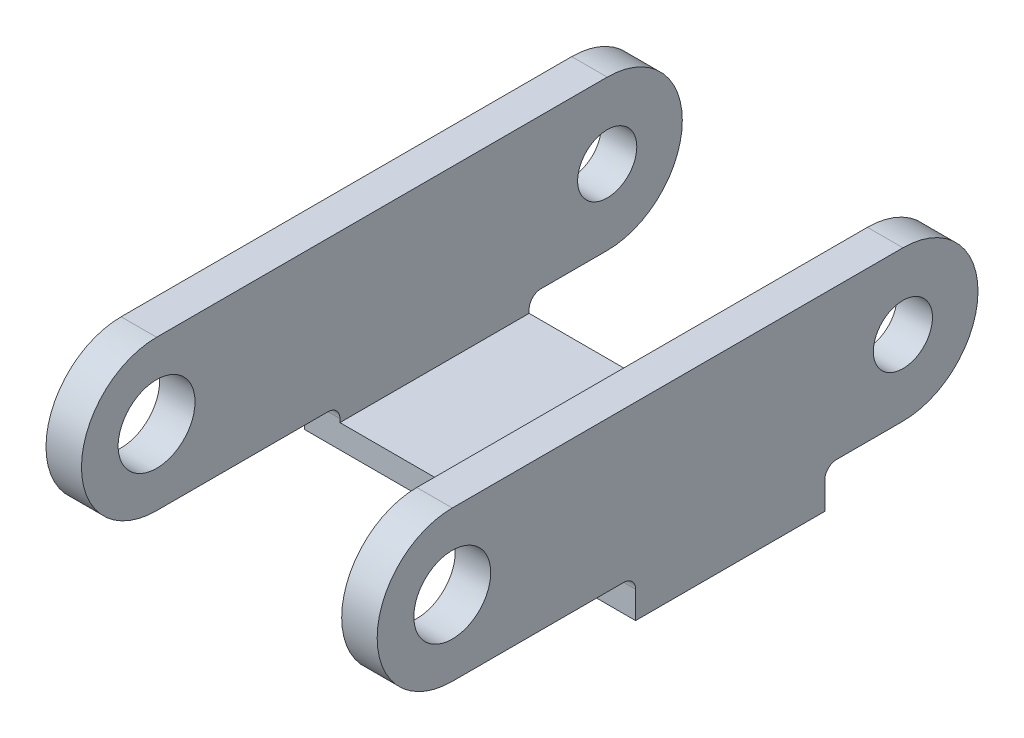
SolidWorks part; units mm, degrees
ref_plane "Front Plane" through (0, 0, 0) normal (0, 0, 1) x (1, 0, 0)
ref_plane "Top Plane" through (0, 0, 0) normal (0, 1, 0) x (1, 0, 0)
ref_plane "Right Plane" through (0, 0, 0) normal (1, 0, 0) x (0, 0, -1)
sketch "Sketch1" plane through (0, 0, 0) normal (1, 0, 0) x (0, 0, -1)
  line L1 (0, 6.35) -> (38.1, 6.35)
  line L3 (15.5, -7.35) -> (15.5, -9.65)
  line L4 (15.5, -9.65) -> (31.5, -9.65)
  line L5 (0, -6.35) -> (14.5, -6.35)
  line L6 (31.5, -9.65) -> (31.5, -7.35)
  line L7 (32.5, -6.35) -> (38.1, -6.35)
  arc A0 (0, 6.35) -> (0, -6.35) centre (0, 0) ccw
  circle A1 centre (0, 0) radius 3.25
  circle A2 centre (38.1, 0) radius 2.5
  arc A3 (38.1, -6.35) -> (38.1, 6.35) centre (38.1, 0) ccw
  arc A4 (15.5, -7.35) -> (14.5, -6.35) centre (14.5, -7.35) ccw
  arc A5 (32.5, -6.35) -> (31.5, -7.35) centre (32.5, -7.35) ccw
  point P10 (31.5, -6.35)
  point P16 (0, 0)
  dimension "D1" = 6.5
  dimension "D2" = 6.35
  dimension "D3" = 1
  dimension "D5" = 5
  dimension "D7" = 1
  dimension "D4" = 38.1
  dimension "D6" = 9.65
  dimension "D8" = 16
  dimension "D9" = 15.5
extrude "Boss-Extrude1" add sketch "Sketch1" along normal blind 3
sketch "Sketch2" plane through (0, 0, 0) normal (0, 1, 0) x (1, 0, 0)
  line L1 (3, 38.1) -> (3, 0) construction
  line L2 (3, 15.5) -> (14, 15.5)
  line L3 (14, 15.5) -> (14, 31.5)
  line L4 (14, 31.5) -> (3, 31.5)
  line L5 (3, 31.5) -> (3, 15.5)
  dimension "D1" = 16
  dimension "D2" = 11
extrude "Boss-Extrude2" add sketch "Sketch2" along normal blind 2 from offset 9.65 offset against normal yes
ref_plane "Plane1" through (14, 0, 0) normal (1, 0, 0) x (0, 0, -1)
mirror "Mirror2" about plane through (14, 0, 0) normal (1, 0, 0) of bodies 102
